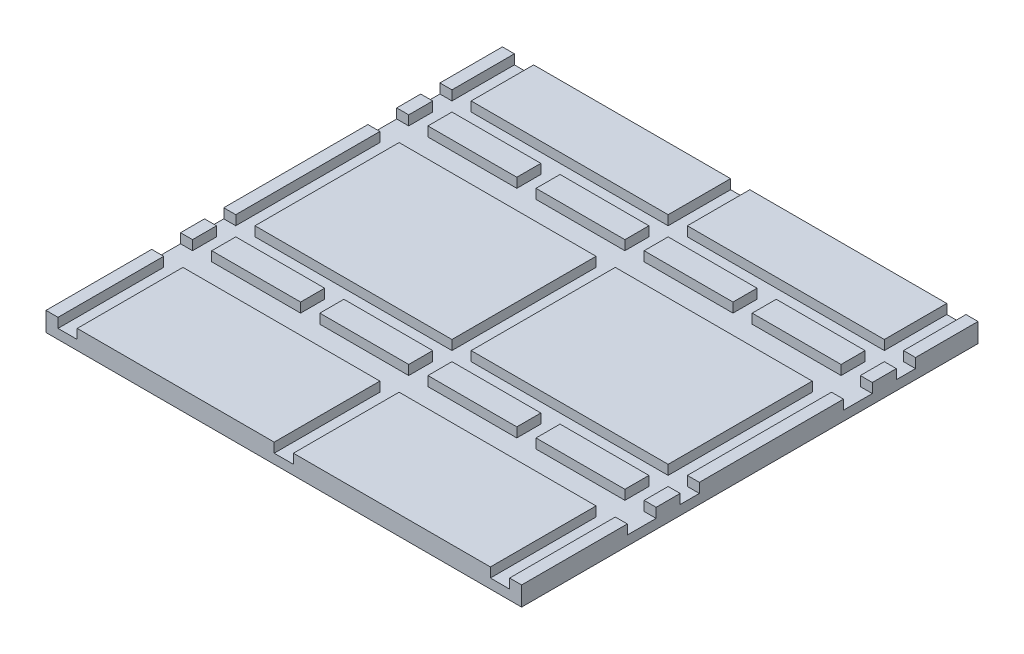
SolidWorks part; units mm, degrees
ref_plane "Front Plane" through (0, 0, 0) normal (0, 0, 1) x (1, 0, 0)
ref_plane "Top Plane" through (0, 0, 0) normal (0, 1, 0) x (1, 0, 0)
ref_plane "Right Plane" through (0, 0, 0) normal (1, 0, 0) x (0, 0, -1)
sketch "Sketch2" plane through (0, 0, 0) normal (0, 1, 0) x (1, 0, 0)
  line L9 (-60.325, -60.325) -> (60.325, -60.325)
  line L10 (-60.325, -60.325) -> (-60.325, 60.325)
  line L11 (-60.325, 60.325) -> (60.325, 60.325)
  line L16 (60.325, -60.325) -> (60.325, 60.325)
  line L17 (-60.325, -60.325) -> (60.325, 60.325) construction
  line L18 (-60.325, 60.325) -> (60.325, -60.325) construction
  point P0 (0, 0)
  dimension "D1" = 120.65
  dimension "D2" = 120.65
extrude "Boss-Extrude1" add sketch "Sketch2" along normal blind 2.54
sketch "Sketch3" plane through (0, 2.54, 0) normal (0, 1, 0) x (1, 0, 0)
  line L0 (57.15, 0) -> (-57.15, 0) construction
  line L5 (-57.15, -57.15) -> (57.15, 57.15) construction
  line L6 (-57.15, 57.15) -> (57.15, -57.15) construction
  line L7 (-57.15, 0) -> (0, 57.15) construction
  line L8 (-2.54, 43.815) -> (-2.54, 60.325)
  line L9 (0, -57.15) -> (57.15, 0) construction
  line L10 (57.15, 0) -> (0, 57.15) construction
  line L11 (0, -57.15) -> (-57.15, 0) construction
  line L12 (-60.325, -24.765) -> (-59.69, -24.765)
  line L13 (-60.325, 60.325) -> (-60.325, -60.325) construction
  line L14 (60.325, -60.325) -> (60.325, 60.325) construction
  line L15 (60.325, -32.385) -> (59.69, -32.385)
  line L16 (-28.575, -28.575) -> (28.575, -28.575) construction
  line L17 (-31.115, -24.765) -> (-31.115, -18.415)
  line L18 (-26.035, -24.765) -> (-26.035, -18.415)
  line L19 (-28.575, -28.575) -> (-28.575, 28.575) construction
  line L20 (28.575, 28.575) -> (28.575, -28.575) construction
  line L21 (-57.15, 57.15) -> (-57.15, -57.15) construction
  line L22 (-57.15, -57.15) -> (57.15, -57.15) construction
  line L23 (57.15, -57.15) -> (57.15, 57.15) construction
  line L24 (57.15, 57.15) -> (-57.15, 57.15) construction
  line L25 (-59.69, 60.325) -> (-59.69, 43.815)
  line L26 (60.325, 60.325) -> (-60.325, 60.325) construction
  line L27 (-60.325, -60.325) -> (60.325, -60.325) construction
  line L28 (-54.61, 60.325) -> (-54.61, 43.815)
  line L29 (-60.325, -15.875) -> (60.325, -15.875) construction
  line L30 (-60.325, -18.415) -> (-59.69, -18.415)
  line L31 (60.325, -13.335) -> (59.69, -13.335)
  line L32 (-26.035, -24.765) -> (-2.54, -24.765)
  line L33 (-26.035, -18.415) -> (-2.54, -18.415)
  line L34 (31.115, -24.765) -> (31.115, -18.415)
  line L35 (26.035, -24.765) -> (26.035, -18.415)
  line L36 (31.115, -24.765) -> (54.61, -24.765)
  line L37 (31.115, -18.415) -> (54.61, -18.415)
  line L38 (-59.69, -13.335) -> (-60.325, -13.335)
  line L39 (-54.61, -18.415) -> (-31.115, -18.415)
  line L40 (-54.61, -24.765) -> (-31.115, -24.765)
  line L41 (-59.69, -32.385) -> (-60.325, -32.385)
  line L42 (59.69, 60.325) -> (59.69, 43.815)
  line L43 (54.61, 60.325) -> (54.61, 43.815)
  line L44 (-54.61, -32.385) -> (-54.61, -60.325)
  line L45 (-54.61, -18.415) -> (-54.61, -24.765)
  line L46 (54.61, -32.385) -> (54.61, -60.325)
  line L47 (59.69, -24.765) -> (60.325, -24.765)
  line L48 (59.69, -18.415) -> (60.325, -18.415)
  line L49 (54.61, -18.415) -> (54.61, -24.765)
  line L50 (54.61, -13.335) -> (2.54, -13.335)
  line L51 (54.61, -32.385) -> (2.54, -32.385)
  line L52 (59.69, -32.385) -> (59.69, -60.325)
  line L53 (59.69, -18.415) -> (59.69, -24.765)
  line L54 (-59.69, -18.415) -> (-59.69, -24.765)
  line L55 (-59.69, -32.385) -> (-59.69, -60.325)
  line L56 (60.325, -60.325) -> (59.69, -60.325)
  line L57 (-60.325, -60.325) -> (-60.325, -32.385)
  line L58 (-60.325, 60.325) -> (-59.69, 60.325)
  line L59 (60.325, 60.325) -> (60.325, 43.815)
  line L60 (-59.69, -60.325) -> (-60.325, -60.325)
  line L61 (54.61, -60.325) -> (2.54, -60.325)
  line L62 (60.325, -32.385) -> (60.325, -60.325)
  line L63 (60.325, -18.415) -> (60.325, -24.765)
  line L64 (-60.325, -13.335) -> (-60.325, 24.765)
  line L65 (-60.325, -24.765) -> (-60.325, -18.415)
  line L66 (-54.61, 32.385) -> (-31.115, 32.385)
  line L67 (54.61, 43.815) -> (2.54, 43.815)
  line L68 (-26.035, 32.385) -> (-2.54, 32.385)
  line L69 (26.035, 32.385) -> (26.035, 38.735)
  line L70 (-26.035, 32.385) -> (-26.035, 38.735)
  line L71 (31.115, 32.385) -> (54.61, 32.385)
  line L72 (-54.61, 38.735) -> (-31.115, 38.735)
  line L73 (-26.035, 38.735) -> (-2.54, 38.735)
  line L74 (-54.61, 38.735) -> (-54.61, 32.385)
  line L75 (31.115, 32.385) -> (31.115, 38.735)
  line L76 (54.61, 24.765) -> (2.54, 24.765)
  line L77 (-31.115, 32.385) -> (-31.115, 38.735)
  line L78 (31.115, 38.735) -> (54.61, 38.735)
  line L79 (54.61, 38.735) -> (54.61, 32.385)
  line L80 (-28.575, 28.575) -> (28.575, 28.575) construction
  line L81 (-54.61, 24.765) -> (-54.61, -13.335)
  line L82 (-54.61, 38.735) -> (-54.61, 32.385)
  line L83 (54.61, 38.735) -> (54.61, 32.385)
  line L84 (54.61, 24.765) -> (54.61, -13.335)
  line L85 (-54.61, 60.325) -> (-2.54, 60.325)
  line L86 (59.69, 60.325) -> (60.325, 60.325)
  line L87 (-59.69, 24.765) -> (-60.325, 24.765)
  line L88 (-59.69, 32.385) -> (-60.325, 32.385)
  line L89 (-59.69, 38.735) -> (-60.325, 38.735)
  line L90 (-59.69, 43.815) -> (-60.325, 43.815)
  line L91 (-59.69, 38.735) -> (-59.69, 32.385)
  line L92 (-60.325, 43.815) -> (-60.325, 60.325)
  line L93 (-59.69, 24.765) -> (-59.69, -13.335)
  line L94 (-60.325, 32.385) -> (-60.325, 38.735)
  line L95 (59.69, 43.815) -> (60.325, 43.815)
  line L96 (59.69, 38.735) -> (60.325, 38.735)
  line L97 (59.69, 32.385) -> (60.325, 32.385)
  line L98 (59.69, 24.765) -> (60.325, 24.765)
  line L99 (59.69, 24.765) -> (59.69, -13.335)
  line L100 (60.325, 24.765) -> (60.325, -13.335)
  line L101 (59.69, 38.735) -> (59.69, 32.385)
  line L102 (60.325, 38.735) -> (60.325, 32.385)
  line L103 (-2.54, -60.325) -> (-2.54, -32.385)
  line L104 (2.54, 60.325) -> (2.54, 43.815)
  line L105 (2.54, 60.325) -> (54.61, 60.325)
  line L106 (-2.54, 43.815) -> (-54.61, 43.815)
  line L107 (2.54, 38.735) -> (26.035, 38.735)
  line L108 (2.54, 32.385) -> (26.035, 32.385)
  line L109 (-2.54, 24.765) -> (-54.61, 24.765)
  line L110 (-2.54, 32.385) -> (-2.54, 38.735)
  line L111 (0, 0) -> (0, -57.15) construction
  line L112 (2.54, 24.765) -> (2.54, -13.335)
  line L113 (2.54, 38.735) -> (2.54, 32.385)
  line L114 (-2.54, -13.335) -> (-54.61, -13.335)
  line L115 (-2.54, -13.335) -> (-2.54, 24.765)
  line L116 (2.54, -18.415) -> (2.54, -24.765)
  line L117 (2.54, -18.415) -> (26.035, -18.415)
  line L118 (2.54, -24.765) -> (26.035, -24.765)
  line L119 (-2.54, -24.765) -> (-2.54, -18.415)
  line L120 (2.54, -32.385) -> (2.54, -60.325)
  line L121 (-2.54, -32.385) -> (-54.61, -32.385)
  line L122 (-2.54, -60.325) -> (-54.61, -60.325)
  point P0 (0, 0)
  line M17 (60.325, -60.325) -> (60.325, 60.325)
  line M18 (60.325, 60.325) -> (-60.325, 60.325)
  line M19 (-60.325, 60.325) -> (-60.325, -60.325)
  line M20 (-60.325, -60.325) -> (60.325, -60.325)
  dimension "D1" = 114.3
  dimension "D2" = 114.3
  dimension "D3" = 7.62
  dimension "D4" = 3.81
  dimension "D5" = 5.08
  dimension "D6" = 2.54
  dimension "D7" = 2.54
  dimension "D8" = 5.08
  dimension "D9" = 12.7
  dimension "D10" = 2.54
  dimension "D11" = 5.08
  dimension "D13" = 5.08
extrude "Boss-Extrude2" add sketch "Sketch3" along normal blind 2.54 contours L39 L45 L40 L17 | L32 L35 L33 L18 | L49 L37 L34 L36 | L46 L51 L44 M20 | L93 L87 L38 M19 | L91 L89 L88 M19 | L90 L25 M18 M19 | L42 L95 M17 M18 | L96 L101 L97 M17 | L98 L99 L31 M17 | L106 L8 L28 M18 | L104 L67 L43 M18 | L76 L112 L50 L84 | L114 L115 L109 L81 | L116 L118 L35 L117 | L51 L120 L46 M20 | L107 L113 L108 L69 | L68 L110 L73 L70 | L54 L12 L65 L30 | L53 L47 L63 L48 | L52 L56 L62 L15 | L55 L60 L57 L41 | L66 L77 L72 L74 | L71 L79 L78 L75
sketch "Sketch5" plane through (60.325, 0, 0) normal (1, 0, 0) x (0, 0, -1)
  line L0 (-60.325, 0) -> (60.325, 0)
  line L1 (60.325, 0) -> (60.325, 5.08)
  line L2 (60.325, 5.08) -> (43.815, 5.08)
  line L3 (43.815, 5.08) -> (43.815, 2.54)
  line L4 (43.815, 2.54) -> (38.735, 2.54)
  line L5 (38.735, 2.54) -> (38.735, 5.08)
  line L6 (38.735, 5.08) -> (32.385, 5.08)
  line L7 (32.385, 5.08) -> (32.385, 2.54)
  line L8 (32.385, 2.54) -> (24.765, 2.54)
  line L9 (24.765, 2.54) -> (24.765, 5.08)
  line L10 (24.765, 5.08) -> (-13.335, 5.08)
  line L11 (-13.335, 5.08) -> (-13.335, 2.54)
  line L12 (-13.335, 2.54) -> (-18.415, 2.54)
  line L13 (-18.415, 2.54) -> (-18.415, 5.08)
  line L14 (-18.415, 5.08) -> (-24.765, 5.08)
  line L15 (-24.765, 5.08) -> (-24.765, 2.54)
  line L16 (-24.765, 2.54) -> (-32.385, 2.54)
  line L17 (-32.385, 2.54) -> (-32.385, 5.08)
  line L18 (-32.385, 5.08) -> (-60.325, 5.08)
  line L19 (-60.325, 5.08) -> (-60.325, 0)
extrude "Boss-Extrude4" add sketch "Sketch5" along normal blind 2.54
mirror "Mirror2" about plane through (0, 0, 0) normal (1, 0, 0) of "Boss-Extrude4"
